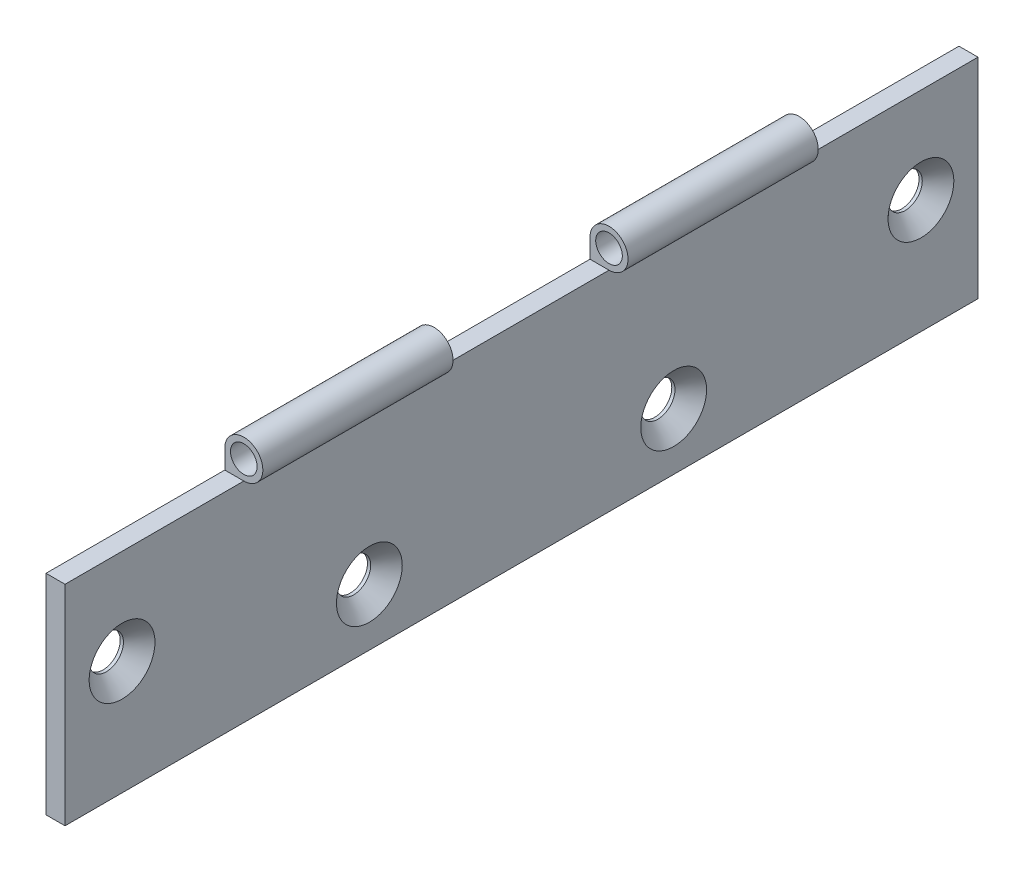
SolidWorks part; units mm, degrees
ref_plane "Front Plane" through (0, 0, 0) normal (0, 0, 1) x (1, 0, 0)
ref_plane "Top Plane" through (0, 0, 0) normal (0, 1, 0) x (1, 0, 0)
ref_plane "Right Plane" through (0, 0, 0) normal (1, 0, 0) x (0, 0, -1)
sketch "Эскиз1" plane through (0, 0, 0) normal (0, 0, 1) x (1, 0, 0)
  line L0 (0, 0) -> (0, 60)
  dimension "D1" = 60
extrude "Вытянуть-Тонкостенный1" add sketch "Эскиз1" along normal mid plane 240 thin
sketch "Эскиз2" plane through (0, 0, 120) normal (0, 0, 1) x (1, 0, 0)
  circle A0 centre (5, 60) radius 5
sweep "По траектории1" add profiles "Эскиз2" path edge at (5, 60, 0)
sketch "Эскиз4" plane through (0, 0, 120) normal (0, 0, 1) x (1, 0, 0)
  circle A0 centre (5, 60) radius 3.5
  arc A1 (5, 55) -> (0, 60) centre (5, 60) ccw construction
extrude "Вырез-Вытянуть1" cut sketch "Эскиз4" against normal through all
hole_wizard "Зенковка для  винта с плоской головкой M81" positions "Эскиз6" profile "Эскиз5" countersink size "M8" standard "Ansi Metric" end condition through all
sketch "Эскиз6" plane through (5, 0, 0) normal (1, 0, 0) x (0, 0, -1)
  point P0 (-105, 30)
  point P2 (-40, 15)
  dimension "D1" = 30
  dimension "D2" = 15
  dimension "D3" = 15
  dimension "D4" = 80
sketch "Эскиз5" plane through (5, 30, 105) normal (0, 1, 0) x (0, 0, -1)
  line L0 (0, 0) -> (0, 5)
  line L1 (0, 5) -> (4.5, 5)
  line L2 (4.5, 5) -> (4.5, 4.15)
  line L3 (4.5, 4.15) -> (8.65, 0)
  line L5 (8.65, 0) -> (0, 0)
  line L6 (-4.5, 4.15) -> (-8.65, 0) construction
  line L11 (0, -6.35) -> (0, 107.95) construction
  dimension "Диаметр сквозного отверстия" = 9
  dimension "Глубина сквозного отверстия" = 5
  dimension "Диаметр передней зенковки" = 17.3
  dimension "Угол передней зенковки" = 90
mirror "Зеркальное отражение1" about plane through (0, 0, 0) normal (0, 0, 1) of "Зенковка для  винта с плоской головкой M81"
sketch "компоновка для вырезов" plane through (5, 0, 0) normal (1, 0, 0) x (0, 0, -1)
  line L5 (-120, 65) -> (-120, 55) construction
  line L6 (120, 54) -> (-120, 54)
  line L7 (120, 54) -> (-120, 54)
  line L8 (120, 55) -> (120, 65) construction
  line L9 (-120, 65) -> (-120, 54)
  line L10 (120, 54) -> (120, 65)
  line L11 (-72, 65) -> (-72, 54)
  line L12 (-24, 65) -> (-24, 54)
  line L13 (120, 65) -> (-120, 65) construction
  line L14 (0, 96.9295) -> (0, 0) construction
  line L15 (24, 65) -> (24, 54)
  line L16 (72, 65) -> (72, 54)
  dimension "D2" = 48
  dimension "D3" = 48
  dimension "D1" = 1
sketch "Эскиз7" plane through (5, 0, 0) normal (1, 0, 0) x (0, 0, -1)
  line L0 (120, 54) -> (120, 65) construction
  line L1 (120, 54) -> (-120, 54) construction
  line L2 (-120, 65) -> (-120, 54) construction
  line L3 (120, 54) -> (120, 65)
  line L4 (120, 0) -> (120, 55)
  line L5 (120, 55) -> (-120, 55)
  line L6 (-120, 55) -> (-120, 0)
  line L7 (-120, 0) -> (120, 0)
  line L8 (120, 0) -> (120, 55)
  line L9 (120, 55) -> (-120, 55)
  line L10 (-120, 55) -> (-120, 0)
  line L11 (-120, 0) -> (120, 0)
  line L12 (120, 54) -> (73, 54)
  line L13 (-120, 65) -> (-120, 54)
  line L14 (120, 65) -> (73, 65)
  line L15 (-73, 65) -> (-120, 65)
  line L16 (-73, 54) -> (-120, 54)
  line L18 (-73, 65) -> (-73, 54)
  line L19 (-73, 65) -> (-73, 54)
  line L20 (23, 65) -> (-23, 65)
  line L21 (-23, 65) -> (-23, 54)
  line L22 (-23, 65) -> (-23, 54)
  line L24 (23, 65) -> (23, 54)
  line L25 (23, 65) -> (23, 54)
  line L26 (23, 54) -> (-23, 54)
  line L27 (73, 65) -> (73, 54)
  line L28 (73, 65) -> (73, 54)
  point P8 (28.8911, 81.2591)
  dimension "D1" = 0
  dimension "D3" = 1
  dimension "D4" = 1
  dimension "D5" = 1
  dimension "D6" = 1
extrude "Вырез-Вытянуть2" cut sketch "Эскиз7" against normal through all both and the other way through all contours L14 L28 L5 L3 | L25 L20 L22 L9 | L19 L15 L13 L9
equation "\"D1@Эскиз6\"= \"D1@Эскиз1\" / 2"
equation "\"D4@Эскиз6\"= \"D1@Вытянуть-Тонкостенный1\" / 3"
equation "\"D2@компоновка для вырезов\"= \"D1@Вытянуть-Тонкостенный1\" / 5"
equation "\"D3@компоновка для вырезов\"= \"D1@Вытянуть-Тонкостенный1\" / 5"
